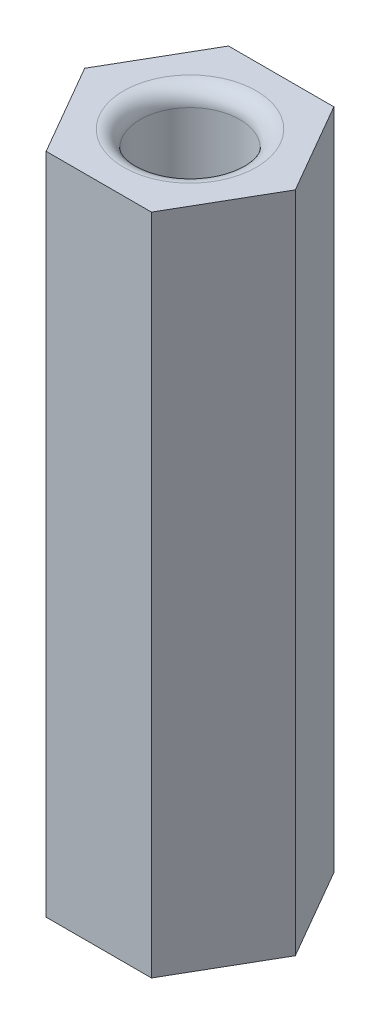
SolidWorks part; units mm, degrees
ref_plane "Front Plane" through (0, 0, 0) normal (0, 0, 1) x (1, 0, 0)
ref_plane "Top Plane" through (0, 0, 0) normal (0, 1, 0) x (1, 0, 0)
ref_plane "Right Plane" through (0, 0, 0) normal (1, 0, 0) x (0, 0, -1)
sketch "Sketch1" plane through (0, 0, 0) normal (0, 1, 0) x (1, 0, 0)
  line L1 (-3.1754, 0) -> (-1.5877, -2.75)
  line L2 (-1.5877, -2.75) -> (1.5877, -2.75)
  line L3 (1.5877, -2.75) -> (3.1754, 0)
  line L4 (3.1754, 0) -> (1.5877, 2.75)
  line L5 (1.5877, 2.75) -> (-1.5877, 2.75)
  line L6 (-1.5877, 2.75) -> (-3.1754, 0)
  circle A0 centre (0, 0) radius 2.75 construction
  circle A1 centre (0, 0) radius 1.5
extrude "Boss-Extrude1" add sketch "Sketch1" along normal blind 20
fillet "Fillet1" radius 0.5 2 edges at (0, 0, 1.5) (0, 20, 1.5)
